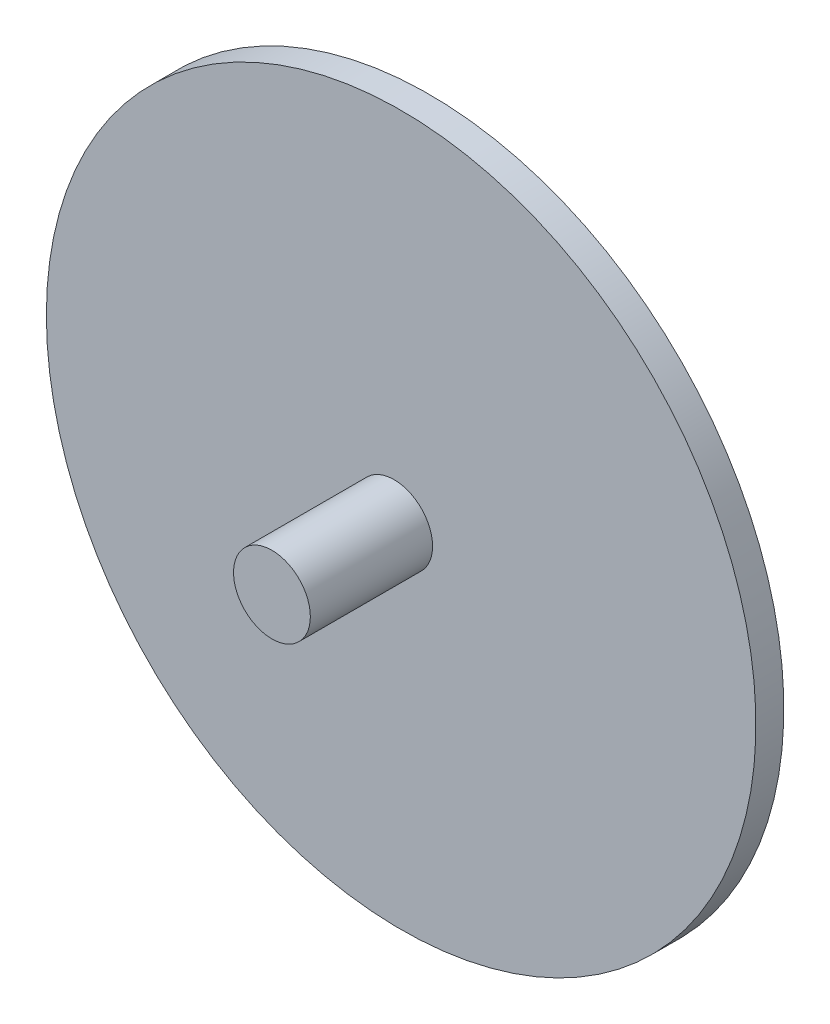
SolidWorks part; units mm, degrees
ref_plane "前视基准面" through (0, 0, 0) normal (0, 0, 1) x (1, 0, 0)
ref_plane "上视基准面" through (0, 0, 0) normal (0, 1, 0) x (1, 0, 0)
ref_plane "右视基准面" through (0, 0, 0) normal (1, 0, 0) x (0, 0, -1)
sketch "草图1" plane through (0, 0, 0) normal (0, 0, 1) x (1, 0, 0)
  circle A0 centre (0, 0) radius 11
  dimension "D1" = 22
extrude "拉伸1" add sketch "草图1" along normal blind 35
sketch "草图2" plane through (0, 0, 0) normal (0, 0, -1) x (-1, 0, 0)
  circle A0 centre (0, 0) radius 3
  dimension "D1" = 6
extrude "拉伸2" add sketch "草图2" along normal blind 10
sketch "草图3" plane through (0, 0, -10) normal (0, 0, -1) x (-1, 0, 0)
  circle A0 centre (0, 0) radius 101.6
  dimension "D1" = 203.2
extrude "拉伸3" add sketch "草图3" against normal blind 8 separate body
